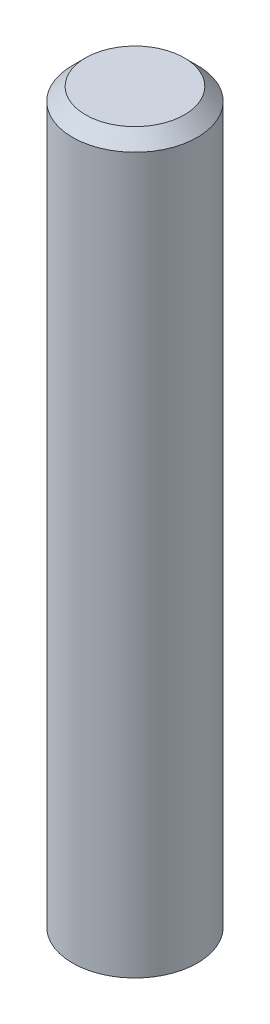
SolidWorks part; units mm, degrees
material "Сплав 2024"
ref_plane "Спереди" through (0, 0, 0) normal (0, 0, 1) x (1, 0, 0)
ref_plane "Сверху" through (0, 0, 0) normal (0, 1, 0) x (1, 0, 0)
ref_plane "Справа" through (0, 0, 0) normal (1, 0, 0) x (0, 0, -1)
sketch "Эскиз1" plane through (0, 0, 0) normal (0, 1, 0) x (1, 0, 0)
  circle A0 centre (0, 0) radius 2.4
  dimension "D1" = 4.8
extrude "Бобышка-Вытянуть1" add sketch "Эскиз1" along normal blind 28
chamfer "Фаска1" distance 0.5 angle 45 1 edges at (0, 28, 2.4)
ref_plane "Плоскость1" through (0, 0, -2.4) normal (0, 0, -1) x (-1, 0, 0)
sketch "Эскиз2" plane through (0, 0, -2.4) normal (0, 0, -1) x (-1, 0, 0)
  line L0 (0, 0) -> (0, 8.1921) construction
  point P3 (0, 9)
  dimension "D1" = 9
hole_wizard "Отверстие обработанное метчиком M3x0.51" positions "Эскиз4" profile "Эскиз3" tap size "M3x0.5" standard "Ansi Metric"
sketch "Эскиз4" plane through (0, 0, -2.4) normal (0, 0, -1) x (-1, 0, 0)
  point P0 (0, 9)
sketch "Эскиз3" plane through (0, 9, -2.4) normal (1, 0, 0) x (0, 1, 0)
  line L0 (0, 0) -> (0, 3.7511)
  line L1 (0, 3.7511) -> (1.25, 3)
  line L2 (1.25, 3) -> (1.25, 0)
  line L5 (1.25, 0) -> (0, 0)
  line L10 (0, 3.7511) -> (-1.25, 3) construction
  line L11 (0, -6.35) -> (0, 107.95) construction
  dimension "Диаметр сверла" = 2.5
  dimension "Глубина сверла" = 3
  dimension "Угол заточки сверла" = 118
